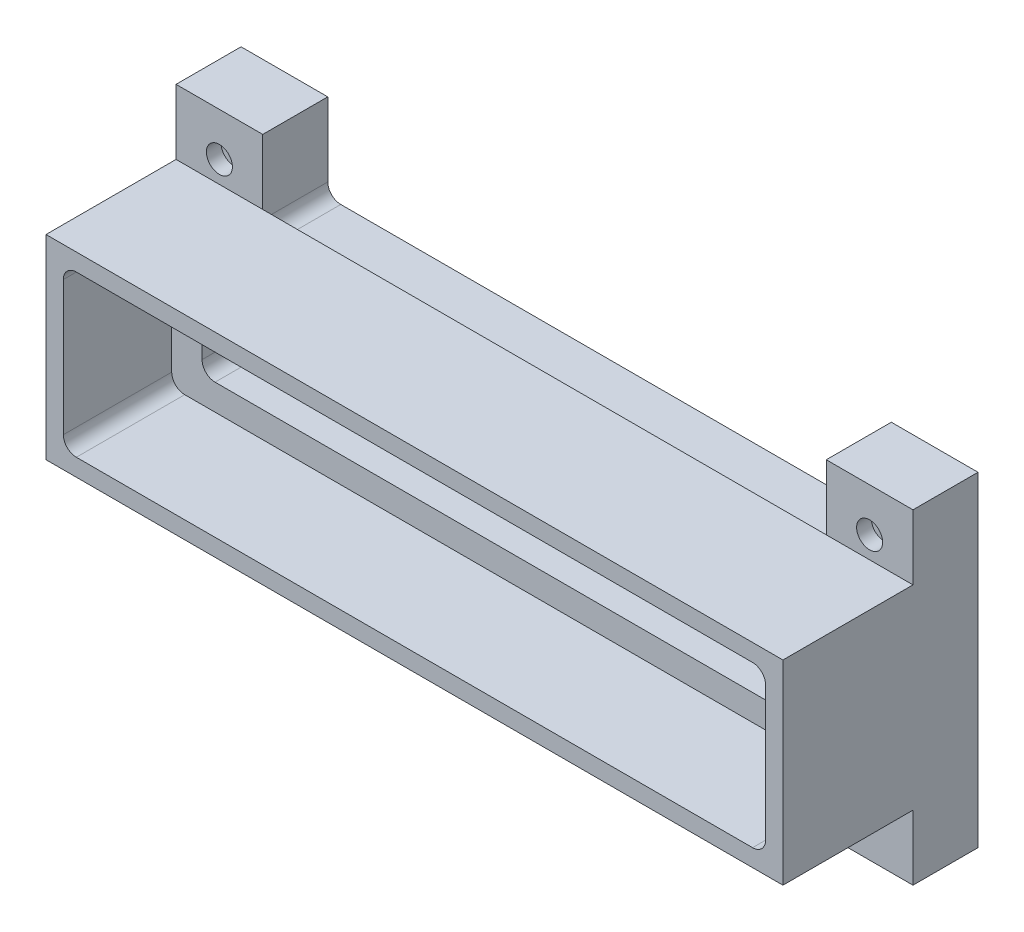
SolidWorks part; units mm, degrees
material "AISI Type 316L stainless steel"
ref_plane "Front Plane" through (0, 0, 0) normal (0, 0, 1) x (1, 0, 0)
ref_plane "Top Plane" through (0, 0, 0) normal (0, 1, 0) x (1, 0, 0)
ref_plane "Right Plane" through (0, 0, 0) normal (1, 0, 0) x (0, 0, -1)
sketch "Sketch1" plane through (0, 0, 0) normal (0, 0, 1) x (1, 0, 0)
  line L5 (85, -37.5) -> (-85, -37.5)
  line L6 (85, -37.5) -> (85, 37.5)
  line L7 (85, 37.5) -> (-85, 37.5)
  line L8 (-85, -37.5) -> (-85, 37.5)
  line L9 (85, -37.5) -> (-85, 37.5) construction
  line L10 (85, 37.5) -> (-85, -37.5) construction
  point P0 (0, 0)
  dimension "D1" = 75
  dimension "D2" = 170
extrude "Boss-Extrude1" add sketch "Sketch1" along normal blind 15 contours L7 L8 L5 L6
sketch "Sketch2" plane through (0, 0, 15) normal (0, 0, 1) x (1, 0, 0)
  line L0 (85, -37.5) -> (-85, -37.5) construction
  line L1 (-65, -37.5) -> (65, -37.5)
  line L2 (-65, -37.5) -> (-65, -17.5)
  line L3 (-65, -17.5) -> (65, -17.5)
  line L4 (65, -37.5) -> (65, -17.5)
  line L5 (-85, -37.5) -> (-85, 37.5) construction
  line L6 (85, -37.5) -> (85, 37.5) construction
  dimension "D1" = 20
  dimension "D2" = 20
  dimension "D3" = 20
extrude "Cut-Extrude1" cut sketch "Sketch2" against normal through all
mirror "Mirror1" about plane through (0, 0, 0) normal (0, 1, 0) of "Cut-Extrude1"
hole_wizard "CBORE for M3 Hexagon socket head cap screws1" positions "Sketch5" profile "Sketch7" counterbore size "M3" standard "GB" end condition through all
sketch "Sketch5" plane through (0, 0, 15) normal (0, 0, 1) x (1, 0, 0)
  line L0 (-85, -37.5) -> (-85, 37.5) construction
  line L1 (-65, 37.5) -> (-85, 37.5) construction
  point P0 (-75, 27.5)
  dimension "D1" = 10
  dimension "D2" = 10
sketch "Sketch7" plane through (-75, 27.5, 15) normal (1, 0, 0) x (0, -1, 0)
  line L0 (0, 0) -> (0, 15)
  line L1 (0, 15) -> (1.6, 15)
  line L3 (1.6, 15) -> (1.6, 3.4)
  line L4 (1.6, 3.4) -> (3, 3.4)
  line L5 (3, 3.4) -> (3, 0)
  line L7 (3, 0) -> (0, 0)
  line L11 (0, -6.35) -> (0, 107.95) construction
  dimension "Thru Hole Dia." = 3.2
  dimension "Thru Hole Depth" = 15
  dimension "C'Bore Dia." = 6
  dimension "C'Bore Depth" = 3.4
mirror "Mirror2" about plane through (0, 0, 0) normal (1, 0, 0) of "CBORE for M3 Hexagon socket head cap screws1" second plane through (0, 0, 0) second plane normal (0, 1, 0)
fillet "Fillet1" radius 3 4 edges at (-65, 17.5, 7.5) (65, 17.5, 7.5) (-65, -17.5, 7.5) (65, -17.5, 7.5)
sketch "Sketch9" plane through (0, 0, 15) normal (0, 0, 1) x (1, 0, 0)
  line L7 (-85, -37.5) -> (-85, 37.5) construction
  line L8 (85, -22.5) -> (-85, -22.5)
  line L9 (85, -22.5) -> (85, 22.5)
  line L10 (85, 22.5) -> (-85, 22.5)
  line L11 (-85, -22.5) -> (-85, 22.5)
  line L12 (85, -22.5) -> (-85, 22.5) construction
  line L13 (85, 22.5) -> (-85, -22.5) construction
  point P0 (0, 0)
  dimension "D1" = 45
extrude "Boss-Extrude3" add sketch "Sketch9" along normal blind 30
sketch "Sketch8" plane through (0, 0, 0) normal (0, 0, -1) x (-1, 0, 0)
  line L1 (74, -12.5) -> (-74, -12.5)
  line L2 (74, -12.5) -> (74, 12.5)
  line L3 (74, 12.5) -> (-74, 12.5)
  line L4 (-74, -12.5) -> (-74, 12.5)
  line L5 (74, -12.5) -> (-74, 12.5) construction
  line L6 (74, 12.5) -> (-74, -12.5) construction
  point P1 (0, 0)
  dimension "D1" = 148
  dimension "D2" = 25
extrude "Cut-Extrude2" cut sketch "Sketch8" against normal through all
sketch "Sketch10" plane through (0, 0, 45) normal (0, 0, 1) x (1, 0, 0)
  line L1 (81, -18.5) -> (-81, -18.5)
  line L2 (81, -18.5) -> (81, 18.5)
  line L3 (81, 18.5) -> (-81, 18.5)
  line L12 (-81, -18.5) -> (-81, 18.5)
  line L13 (81, -18.5) -> (-81, 18.5) construction
  line L14 (81, 18.5) -> (-81, -18.5) construction
  line L16 (85, 22.5) -> (-85, 22.5) construction
  line L17 (-85, 22.5) -> (-85, -22.5) construction
  point P0 (0, 0)
  dimension "D1" = 4
  dimension "D2" = 4
extrude "Cut-Extrude3" cut sketch "Sketch10" against normal blind 25
fillet "Fillet2" radius 3 8 edges at (-81, 18.5, 32.5) (81, -18.5, 32.5) (-81, -18.5, 32.5) (81, 18.5, 32.5) (-74, 12.5, 10) (-74, -12.5, 10) (74, -12.5, 10) (74, 12.5, 10)
sketch "Sketch11" plane through (-85, 0, 0) normal (-1, 0, 0) x (0, 0, 1)
  line L0 (24.75, 0) -> (-24.75, 0) construction
  line L1 (45, 22.5) -> (45, -22.5) construction
  point P0 (37, 13)
  point P2 (27, 5)
  point P4 (27, -5)
  point P5 (37, -13)
  dimension "D1" = 10
  dimension "D2" = 10
  dimension "D3" = 8
  dimension "D4" = 8
